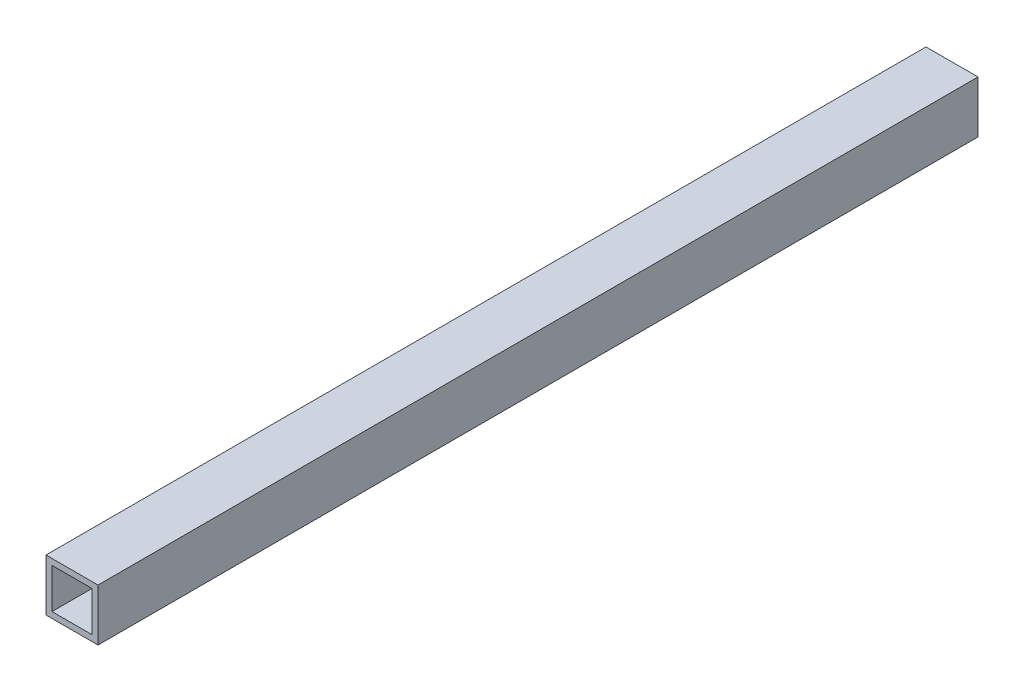
SolidWorks part; units mm, degrees
ref_plane "Front Plane" through (0, 0, 0) normal (0, 0, 1) x (1, 0, 0)
ref_plane "Top Plane" through (0, 0, 0) normal (0, 1, 0) x (1, 0, 0)
ref_plane "Right Plane" through (0, 0, 0) normal (1, 0, 0) x (0, 0, -1)
sketch "Sketch1" plane through (0, 0, 0) normal (0, 0, 1) x (1, 0, 0)
  line L1 (-6.5, 6.5) -> (6.5, 6.5)
  line L2 (-6.5, 6.5) -> (-6.5, -6.5)
  line L3 (-6.5, -6.5) -> (6.5, -6.5)
  line L4 (6.5, 6.5) -> (6.5, -6.5)
  line L5 (-6.5, 6.5) -> (6.5, -6.5) construction
  line L6 (-6.5, -6.5) -> (6.5, 6.5) construction
  line L7 (-5, -5) -> (5, -5)
  line L8 (-5, -5) -> (-5, 5)
  line L9 (-5, 5) -> (5, 5)
  line L10 (5, -5) -> (5, 5)
  line L11 (-5, -5) -> (5, 5) construction
  line L12 (-5, 5) -> (5, -5) construction
  point P0 (0, 0)
  point P6 (0, 0)
  dimension "D1" = 13
  dimension "D2" = 13
  dimension "D3" = 1.5
extrude "Boss-Extrude1" add sketch "Sketch1" along normal blind 220
ref_plane "Plane1" through (0, 0, 110) normal (0, 0, 1) x (1, 0, 0)
